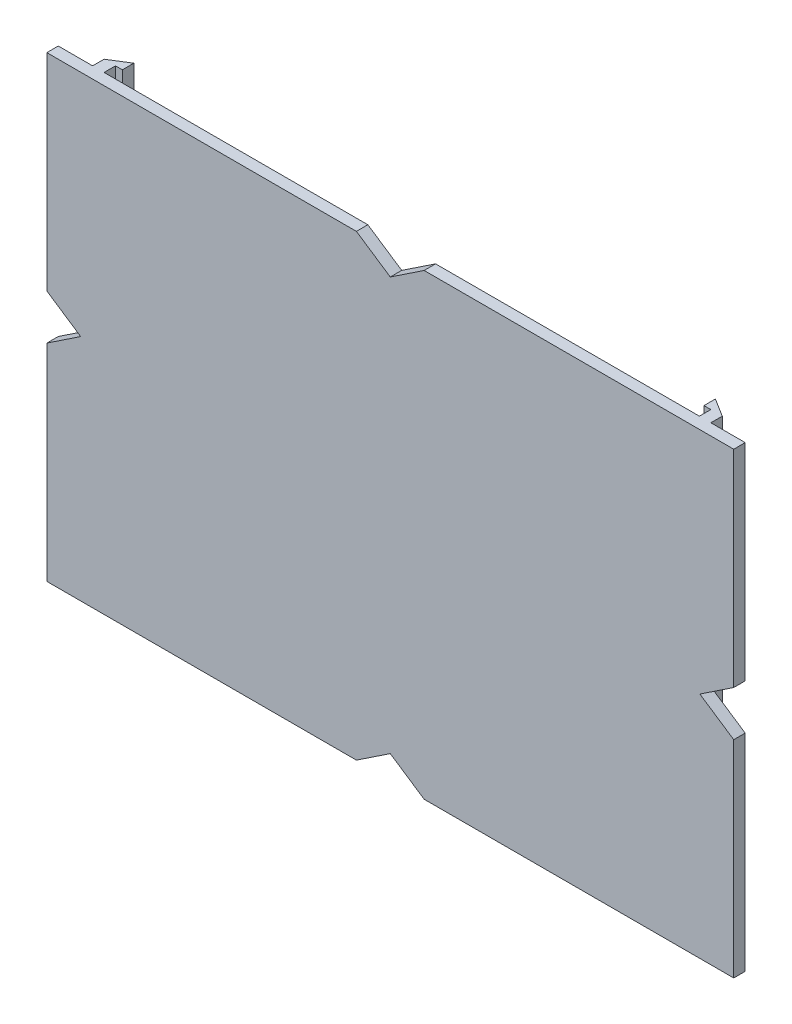
SolidWorks part; units mm, degrees
ref_plane "Front Plane" through (0, 0, 0) normal (0, 0, 1) x (1, 0, 0)
ref_plane "Top Plane" through (0, 0, 0) normal (0, 1, 0) x (1, 0, 0)
ref_plane "Right Plane" through (0, 0, 0) normal (1, 0, 0) x (0, 0, -1)
sketch "Sketch1" plane through (0, 0, 0) normal (0, 0, 1) x (1, 0, 0)
  line L0 (-150, 9.8612) -> (-135.2082, 0)
  line L1 (-150, 100) -> (150, 100)
  line L2 (-150, 100) -> (-150, -100)
  line L3 (-150, -100) -> (150, -100)
  line L4 (150, 100) -> (150, -100)
  line L5 (-150, 100) -> (150, -100) construction
  line L6 (-150, -100) -> (150, 100) construction
  line L7 (-14.7918, -100) -> (0, -90.1388)
  line L8 (-14.7918, 100) -> (0, 90.1388)
  line L9 (-150, -9.8612) -> (-135.2082, 0)
  line L10 (0, 90.1388) -> (14.7918, 100)
  line L11 (-191.6025, -37.5962) -> (108.3975, 162.4038) construction
  line L12 (0, -90.1388) -> (14.7918, -100)
  line L13 (-191.6025, 37.5962) -> (108.3975, -162.4038) construction
  line L14 (135.2082, 0) -> (150, 9.8612)
  line L15 (-108.3975, -162.4038) -> (191.6025, 37.5962) construction
  line L16 (135.2082, 0) -> (150, -9.8612)
  line L17 (-108.3975, 162.4038) -> (191.6025, -37.5962) construction
  point P0 (0, 0)
  dimension "D1" = 300
  dimension "D2" = 200
  dimension "D3" = 75
  dimension "D4" = 75
extrude "Boss-Extrude1" add sketch "Sketch1" along normal blind 5 contours L16 L14 L4 L1 L10 L8 L2 L0 L9 L3 L7 L12
sketch "Sketch2" plane through (0, 100, 0) normal (0, 1, 0) x (1, 0, 0)
  line L0 (-130, 0) -> (-130, 5)
  line L1 (-150, 0) -> (-14.7918, 0) construction
  line L2 (-130, 5) -> (-127, 5)
  line L3 (-127, 5) -> (-127, 10)
  line L4 (-127, 10) -> (-135, 5)
  line L6 (-135, 5) -> (-135, 0)
  line L10 (-14.7918, 0) -> (-150, 0)
  line L11 (-150, 0) -> (-150, -5)
  line L12 (-150, -5) -> (-14.7918, -5)
  line L13 (-14.7918, 0) -> (-150, 0)
  line L18 (-14.7918, -5) -> (-14.7918, 0)
  line L19 (-14.7918, -5) -> (-14.7918, 0)
  line M11 (-14.7918, 0) -> (-150, 0)
  dimension "D1" = 5
  dimension "D2" = 5
  dimension "D3" = 3
  dimension "D4" = 5
  dimension "D5" = 130
  dimension "D6" = 5
  dimension "D7" = 0
extrude "Boss-Extrude2" add sketch "Sketch2" against normal up to surface (200 mm away) contours L4 L6 L0 L2 L3 M11 up to face at (-82.3959, -100, 2.5)
mirror "Mirror1" about plane through (0, 0, 0) normal (1, 0, 0) of "Boss-Extrude2"
